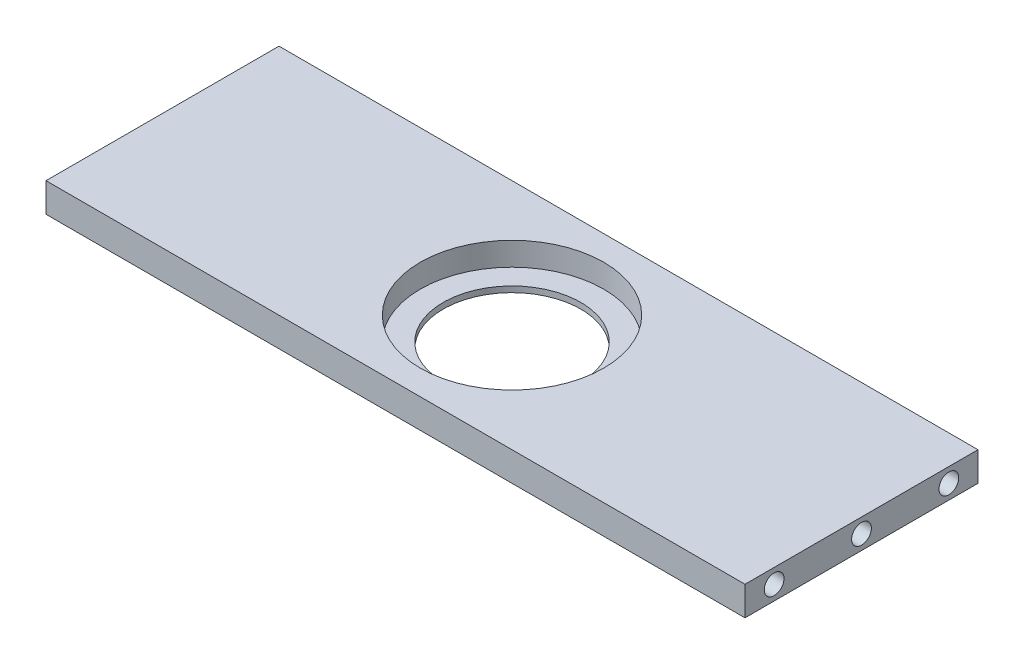
SolidWorks part; units mm, degrees
ref_plane "Front Plane" through (0, 0, 0) normal (0, 0, 1) x (1, 0, 0)
ref_plane "Top Plane" through (0, 0, 0) normal (0, 1, 0) x (1, 0, 0)
ref_plane "Right Plane" through (0, 0, 0) normal (1, 0, 0) x (0, 0, -1)
sketch "Sketch1" plane through (0, 0, 0) normal (0, 1, 0) x (1, 0, 0)
  line L1 (-76.2, -25.4) -> (76.2, -25.4)
  line L2 (-76.2, -25.4) -> (-76.2, 25.4)
  line L3 (-76.2, 25.4) -> (76.2, 25.4)
  line L4 (76.2, -25.4) -> (76.2, 25.4)
  line L5 (-76.2, -25.4) -> (76.2, 25.4) construction
  line L6 (-76.2, 25.4) -> (76.2, -25.4) construction
  point P0 (0, 0)
  dimension "D1" = 50.8
  dimension "D2" = 152.4
extrude "Boss-Extrude1" add sketch "Sketch1" against normal blind 6.35
sketch "Sketch2" plane through (0, 0, 0) normal (0, 1, 0) x (1, 0, 0)
  circle A0 centre (0, 0) radius 20
  dimension "D1" = 40
extrude "Cut-Extrude1" cut sketch "Sketch2" against normal blind 5.08
sketch "Sketch3" plane through (0, -5.08, 0) normal (0, 1, 0) x (1, 0, 0)
  circle A0 centre (0, 0) radius 15
  dimension "D1" = 30
extrude "Cut-Extrude2" cut sketch "Sketch3" against normal through all
sketch "Sketch5" plane through (-76.2, 0, 0) normal (-1, 0, 0) x (0, 0, 1)
  line L0 (-25.4, 0) -> (25.4, 0) construction
  line L1 (0, 0) -> (0, -6.35) construction
  line L2 (-25.4, -6.35) -> (25.4, -6.35) construction
  circle A0 centre (0, -3.175) radius 2.1526
  circle A1 centre (19.05, -3.175) radius 2.1527
  circle A2 centre (-19.05, -3.175) radius 2.1527
  point P5 (0, 0)
  dimension "D1" = 4.3053
  dimension "D2" = 3.175
  dimension "D4" = 19.05
  dimension "D5" = 3.175
  dimension "D3" = 2
extrude "Cut-Extrude4" cut sketch "Sketch5" against normal blind 25.4
mirror "Mirror1" about plane through (0, 0, 0) normal (1, 0, 0) of "Cut-Extrude4"
